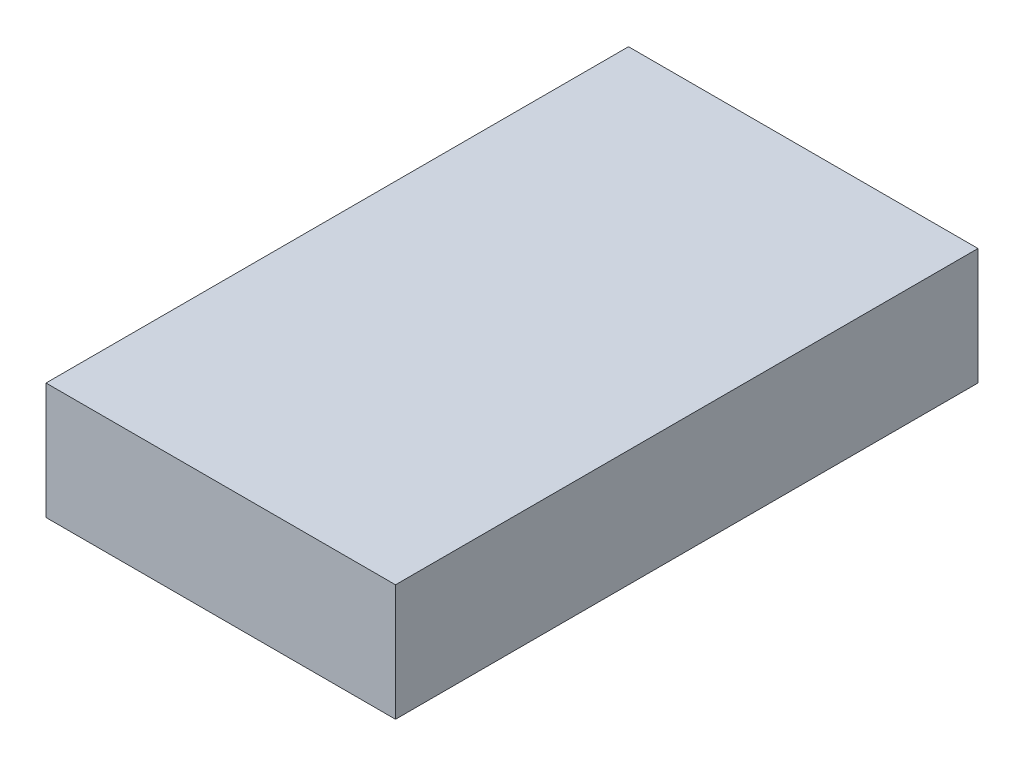
SolidWorks part; units mm, degrees
ref_plane "前视基准面" through (0, 0, 0) normal (0, 0, 1) x (1, 0, 0)
ref_plane "上视基准面" through (0, 0, 0) normal (0, 1, 0) x (1, 0, 0)
ref_plane "右视基准面" through (0, 0, 0) normal (1, 0, 0) x (0, 0, -1)
sketch "草图1" plane through (0, 0, 0) normal (0, 0, 1) x (1, 0, 0)
  line L1 (-93.6522, 100.4348) -> (86.3478, 100.4348)
  line L2 (-93.6522, 100.4348) -> (-93.6522, 40.4348)
  line L3 (-93.6522, 40.4348) -> (86.3478, 40.4348)
  line L4 (86.3478, 100.4348) -> (86.3478, 40.4348)
  dimension "D1" = 180
  dimension "D2" = 60
extrude "凸台-拉伸1" add sketch "草图1" along normal blind 300
